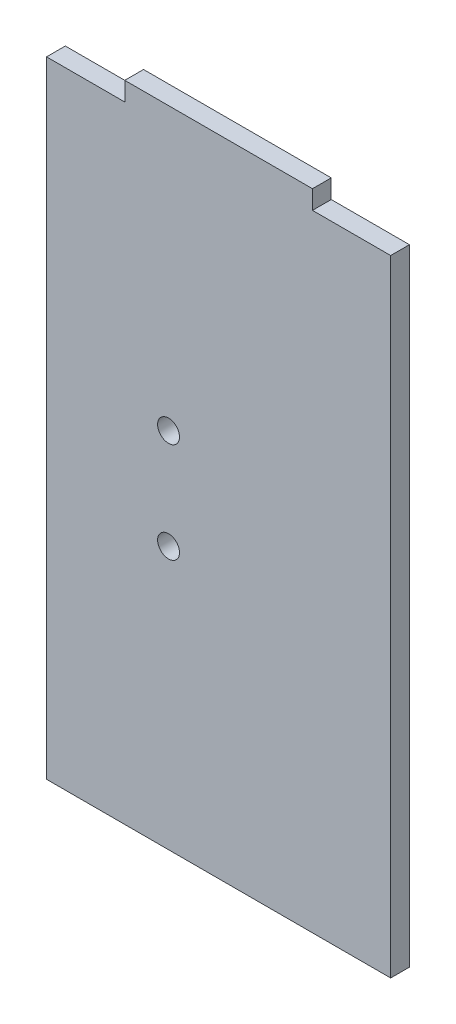
SolidWorks part; units mm, degrees
material "ABS"
ref_plane "Спереди" through (0, 0, 0) normal (0, 0, 1) x (1, 0, 0)
ref_plane "Сверху" through (0, 0, 0) normal (0, 1, 0) x (1, 0, 0)
ref_plane "Справа" through (0, 0, 0) normal (1, 0, 0) x (0, 0, -1)
sketch "Эскиз1" plane through (0, 0, 0) normal (0, 0, 1) x (1, 0, 0)
  line L1 (-27.5, -50) -> (27.5, -50)
  line L2 (-27.5, -50) -> (-27.5, 50)
  line L3 (-27.5, 50) -> (27.5, 50)
  line L4 (27.5, -50) -> (27.5, 50)
  line L5 (-27.5, -50) -> (27.5, 50) construction
  line L6 (-27.5, 50) -> (27.5, -50) construction
  line L7 (-15, 47) -> (15, 47)
  line L8 (-15, 47) -> (-15, 53)
  line L9 (-15, 53) -> (15, 53)
  line L10 (15, 47) -> (15, 53)
  line L11 (-15, 47) -> (15, 53) construction
  line L12 (-15, 53) -> (15, 47) construction
  point P0 (0, 0)
  point P6 (0, 50)
  dimension "D1" = 3
  dimension "D2" = 30
  dimension "D3" = 12.5
  dimension "D4" = 100
extrude "Бобышка-Вытянуть1" add sketch "Эскиз1" along normal blind 3 contours L10 L7 L8 L3 L2 L1 L4 | L7 L10 L3 L8 | L3 L10 L9 L8
sketch "Эскиз2" plane through (0, 0, 3) normal (0, 0, 1) x (1, 0, 0)
  line L0 (-8, -50) -> (-8, 48.9753) construction
  line L1 (-27.5, -50) -> (27.5, -50) construction
  line L2 (0, 0) -> (-27.5, 0) construction
  line L3 (-27.5, -50) -> (-27.5, 50) construction
  circle A0 centre (-8, 8) radius 1.75
  circle A1 centre (-8, -8) radius 1.75
  dimension "D1" = 3.5
  dimension "D2" = 8
  dimension "D3" = 8
extrude "Вырез-Вытянуть1" cut sketch "Эскиз2" against normal blind 10
